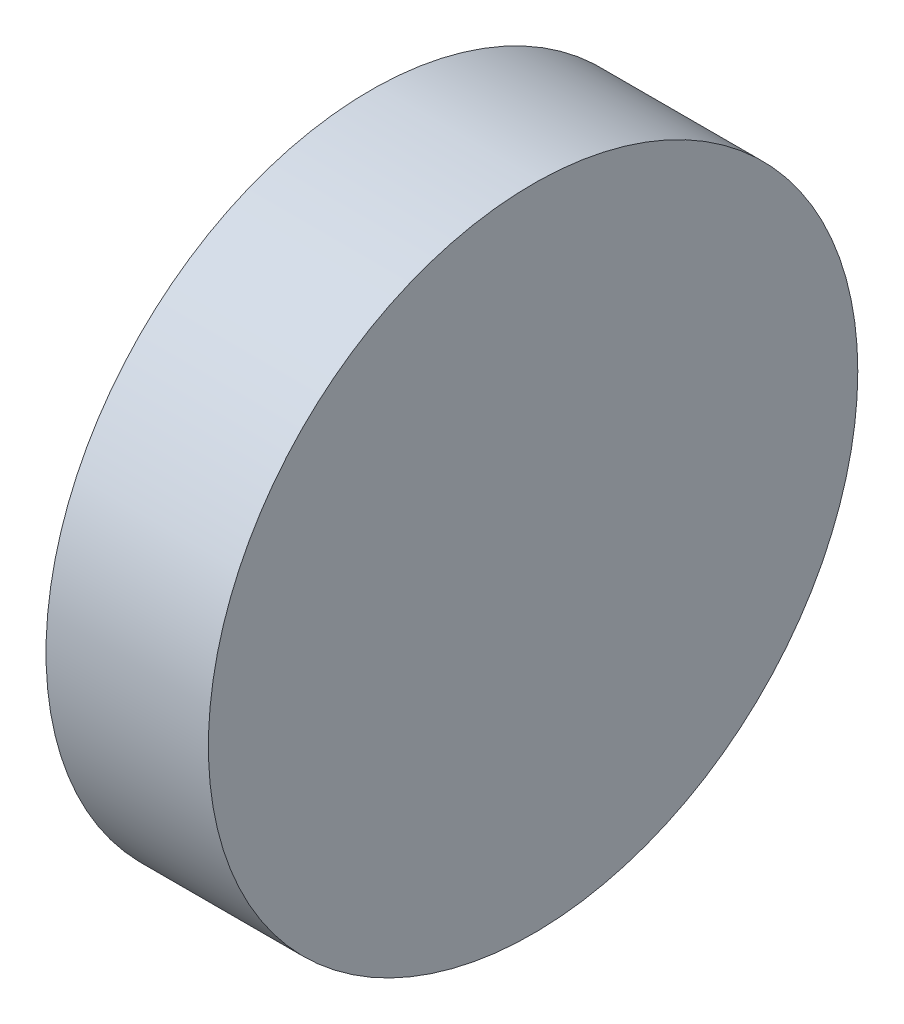
SolidWorks part; units mm, degrees
ref_plane "前视基准面" through (0, 0, 0) normal (0, 0, 1) x (1, 0, 0)
ref_plane "上视基准面" through (0, 0, 0) normal (0, 1, 0) x (1, 0, 0)
ref_plane "右视基准面" through (0, 0, 0) normal (1, 0, 0) x (0, 0, -1)
sketch "草图1" plane through (0, 0, 0) normal (1, 0, 0) x (0, 0, -1)
  circle A0 centre (0, 0) radius 200
extrude "凸台-拉伸1" add sketch "草图1" along normal blind 100
